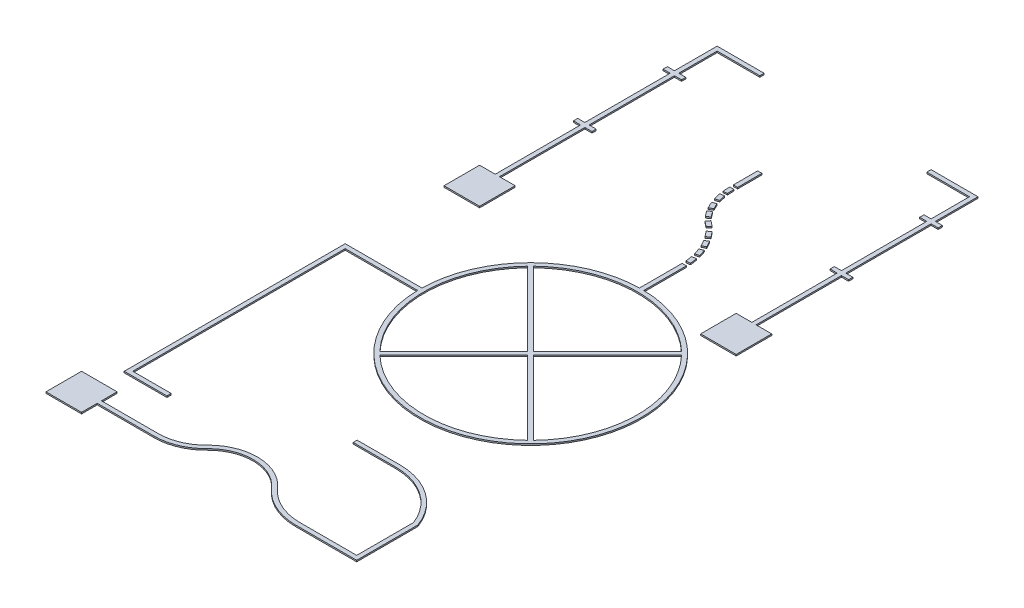
SolidWorks part; units mm, degrees
ref_plane "Front Plane" through (0, 0, 0) normal (0, 0, 1) x (1, 0, 0)
ref_plane "Top Plane" through (0, 0, 0) normal (0, 1, 0) x (1, 0, 0)
ref_plane "Right Plane" through (0, 0, 0) normal (1, 0, 0) x (0, 0, -1)
sketch "Sketch1" plane through (0, 0, 0) normal (0, 1, 0) x (1, 0, 0)
  line L1 (1219.2, -2438.4) -> (-1219.2, -2438.4)
  line L2 (1219.2, -2438.4) -> (1219.2, 2438.4)
  line L3 (1219.2, 2438.4) -> (-1219.2, 2438.4)
  line L4 (-1219.2, -2438.4) -> (-1219.2, 2438.4)
  line L5 (1219.2, -2438.4) -> (-1219.2, 2438.4) construction
  line L6 (1219.2, 2438.4) -> (-1219.2, -2438.4) construction
  point P0 (0, 0)
  dimension "D1" = 4876.8
  dimension "D2" = 2438.4
extrude "Boss-Extrude1" add sketch "Sketch1" along normal blind 100
sketch "Sketch2" plane through (0, 100, 0) normal (0, 1, 0) x (1, 0, 0)
  line L0 (-1219.2, 2438.4) -> (-1219.2, -2438.4) construction
  line L1 (-919.2, -2338.4) -> (-1169.2, -2338.4)
  line L2 (-919.2, -2338.4) -> (-919.2, -2228.4)
  line L3 (-919.2, -2088.4) -> (-1169.2, -2088.4)
  line L4 (-1169.2, -2338.4) -> (-1169.2, -2088.4)
  line L5 (-919.2, -2338.4) -> (-1169.2, -2088.4) construction
  line L6 (-919.2, -2088.4) -> (-1169.2, -2338.4) construction
  line L7 (-1219.2, -2438.4) -> (1219.2, -2438.4) construction
  line L8 (-919.2, -2228.4) -> (-519.2, -2228.4)
  line L9 (-919.2, -2213.4) -> (-874.2776, -2213.4) construction
  line L10 (-919.2, -2198.4) -> (-519.2, -2198.4)
  line L11 (-919.2, -2198.4) -> (-919.2, -2088.4)
  line L12 (518.6973, -2271.9533) -> (948.6973, -2271.9533)
  line L13 (518.6973, -2241.9533) -> (918.6973, -2241.9533)
  line L14 (918.6973, -2241.9533) -> (918.6973, -1841.9533)
  line L15 (948.6973, -2271.9533) -> (948.6973, -1841.9533)
  line L17 (518.6973, -1539.0748) -> (218.6973, -1539.0748)
  line L18 (218.6973, -1539.0748) -> (218.6973, -1567.2032)
  line L19 (218.6973, -1567.2032) -> (518.6973, -1567.2032)
  line L20 (-1019.2, -1938.4) -> (-719.2, -1938.4)
  line L21 (-719.2, -1938.4) -> (-719.2, -1908.4)
  line L22 (-719.2, -1908.4) -> (-989.2, -1908.4)
  line L23 (-989.2, -1908.4) -> (-989.2, -415)
  line L24 (-989.2, -415) -> (-479.8558, -415)
  line L25 (300, -400) -> (-1082.2018, -400) construction
  line L26 (-1019.2, -1938.4) -> (-1019.2, -385)
  line L27 (-1019.2, -385) -> (-479.8558, -385)
  line L28 (300, -400) -> (300, -1150) construction
  line L29 (300, -400) -> (830.3301, -930.3301) construction
  line L30 (819.6179, -940.8301) -> (300, -421.2121)
  line L31 (300, -400) -> (-230.3301, 130.3301) construction
  line L32 (840.8301, -919.6179) -> (321.2121, -400)
  line L33 (300, -400) -> (830.3301, 130.3301) construction
  line L34 (830.3301, 130.3301) -> (-230.3301, -930.3301) construction
  line L35 (-240.8301, -919.6179) -> (278.7879, -400)
  line L36 (840.8301, 119.6179) -> (321.2121, -400)
  line L37 (300, -378.7879) -> (819.6179, 140.8301)
  line L38 (278.7879, -400) -> (-240.8301, 119.6179)
  line L39 (300, -421.2121) -> (-219.6179, -940.8301)
  line L40 (300, -378.7879) -> (-219.6179, 140.8301)
  line L41 (300, -400) -> (300, 350) construction
  line L42 (300, 350) -> (300, 632.1211) construction
  line L43 (285, 379.8558) -> (285, 679.8558)
  line L44 (315, 379.8558) -> (315, 679.8558)
  line L45 (285, 679.8558) -> (315, 679.8558)
  line L47 (283.4854, 707.2433) -> (313.3638, 709.8558)
  line L48 (276.8899, 753.4856) -> (306.3073, 759.3304)
  line L49 (270.3336, 781.5256) -> (299.2927, 789.3304)
  line L50 (255.7416, 825.8982) -> (283.6807, 836.8045)
  line L51 (243.6288, 853.9382) -> (270.7213, 866.8045)
  line L52 (221.3238, 894.9789) -> (246.8572, 910.7139)
  line L53 (202.4819, 923.0189) -> (226.6982, 940.7139)
  line L54 (172.9117, 959.1776) -> (195.0611, 979.4001)
  line L55 (144.8258, 987.2176) -> (165.012, 1009.4001)
  line L57 (104.4289, 1065.1132) -> (81.255, 1046.0708)
  line L58 (77.2262, 1102.6314) -> (51.9232, 1086.5256)
  line L59 (64.2637, 1124.5744) -> (37.9461, 1110.1861)
  line L60 (16.6704, 1155.4) -> (44.5324, 1166.5062)
  line L61 (34.3337, 1195.4) -> (5.6734, 1186.5553)
  line L62 (23.3708, 1240.4268) -> (-6.1476, 1235.1065)
  line L63 (-10.1201, 1262.2983) -> (19.6866, 1265.6449)
  line L64 (-12.6825, 1312.2021) -> (17.3102, 1311.9261)
  line L65 (18.3921, 1337.3888) -> (17.294, 1337.4721)
  line L66 (-12.7, 1337.4721) -> (-12.7, 1508.4)
  line L67 (-12.7, 1508.4) -> (17.294, 1508.4)
  line L68 (17.294, 1508.4) -> (17.294, 1337.4721)
  line L69 (2.297, 1508.4) -> (2.297, 2375.9732) construction
  line L70 (-584.703, 2095.4) -> (-884.703, 2095.4)
  line L71 (-584.703, 2095.4) -> (-584.703, 2125.4)
  line L72 (-584.703, 2125.4) -> (-914.703, 2125.4)
  line L73 (-914.703, 2125.4) -> (-914.703, 1825.4)
  line L75 (-884.703, 1825.4) -> (-884.703, 2095.4)
  line L82 (1219.2, 2438.4) -> (-1219.2, 2438.4) construction
  line L83 (126.2742, 1040.9739) -> (108.6188, 1016.7287)
  line L84 (-914.703, 1795.4) -> (-914.703, 1195.4)
  line L86 (-884.703, 565.4) -> (-884.703, 1165.4)
  line L87 (-884.703, 1825.4) -> (-834.703, 1825.4)
  line L88 (-834.703, 1825.4) -> (-834.703, 1795.4)
  line L89 (-834.703, 1795.4) -> (-884.703, 1795.4)
  line L90 (-884.703, 1195.4) -> (-834.703, 1195.4)
  line L91 (-914.703, 1795.4) -> (-964.703, 1795.4)
  line L92 (-964.703, 1795.4) -> (-964.703, 1825.4)
  line L93 (-964.703, 1825.4) -> (-914.703, 1825.4)
  line L94 (-834.703, 1195.4) -> (-834.703, 1165.4)
  line L95 (-834.703, 1165.4) -> (-884.703, 1165.4)
  line L96 (-899.703, 565.4) -> (-899.703, 505.0509) construction
  line L97 (-914.703, 1165.4) -> (-964.703, 1165.4)
  line L98 (-964.703, 1165.4) -> (-964.703, 1195.4)
  line L99 (-964.703, 1195.4) -> (-914.703, 1195.4)
  line L100 (-884.703, 1195.4) -> (-884.703, 1795.4)
  line L101 (-914.703, 1165.4) -> (-914.703, 565.4)
  line L102 (-884.703, 565.4) -> (-774.703, 565.4)
  line L103 (-774.703, 565.4) -> (-774.703, 315.4)
  line L104 (-774.703, 315.4) -> (-1024.703, 315.4)
  line L105 (-1024.703, 315.4) -> (-1024.703, 565.4)
  line L106 (-1024.703, 565.4) -> (-914.703, 565.4)
  line L107 (17.294, 1337.4721) -> (-12.7, 1337.4721)
  line L108 (17.294, 1311.9263) -> (17.294, 1308.4)
  line L109 (889.297, 565.4) -> (779.297, 565.4)
  line L110 (779.297, 565.4) -> (779.297, 315.4)
  line L111 (779.297, 315.4) -> (1029.297, 315.4)
  line L112 (1029.297, 315.4) -> (1029.297, 565.4)
  line L113 (1029.297, 565.4) -> (919.297, 565.4)
  line L114 (919.297, 1165.4) -> (919.297, 565.4)
  line L115 (919.297, 1165.4) -> (969.297, 1165.4)
  line L116 (969.297, 1165.4) -> (969.297, 1195.4)
  line L117 (969.297, 1195.4) -> (919.297, 1195.4)
  line L118 (919.297, 1795.4) -> (919.297, 1195.4)
  line L119 (919.297, 1795.4) -> (969.297, 1795.4)
  line L120 (969.297, 1795.4) -> (969.297, 1825.4)
  line L121 (969.297, 1825.4) -> (919.297, 1825.4)
  line L122 (919.297, 2125.4) -> (919.297, 1825.4)
  line L123 (589.297, 2125.4) -> (919.297, 2125.4)
  line L124 (589.297, 2095.4) -> (589.297, 2125.4)
  line L125 (589.297, 2095.4) -> (889.297, 2095.4)
  line L126 (889.297, 1825.4) -> (889.297, 2095.4)
  line L127 (889.297, 1825.4) -> (839.297, 1825.4)
  line L128 (839.297, 1825.4) -> (839.297, 1795.4)
  line L129 (839.297, 1795.4) -> (889.297, 1795.4)
  line L130 (889.297, 1195.4) -> (889.297, 1795.4)
  line L131 (889.297, 1195.4) -> (839.297, 1195.4)
  line L132 (839.297, 1195.4) -> (839.297, 1165.4)
  line L133 (839.297, 1165.4) -> (889.297, 1165.4)
  line L134 (889.297, 565.4) -> (889.297, 1165.4)
  arc A0 (-519.2, -2228.4) -> (-256.4254, -2117.5698) centre (-519.2, -1861.47) ccw
  arc A1 (-519.2, -2198.4) -> (-277.9097, -2096.6312) centre (-519.2, -1861.47) ccw
  arc A3 (208.9279, -2130.8016) -> (-256.4254, -2117.5698) centre (-29.8396, -2338.4) ccw
  arc A4 (231.5673, -2111.1176) -> (518.6973, -2241.9533) centre (518.6973, -1861.47) ccw
  arc A5 (208.9279, -2130.8016) -> (518.6973, -2271.9533) centre (518.6973, -1861.47) ccw
  arc A6 (231.5673, -2111.1176) -> (-277.9097, -2096.6312) centre (-29.8396, -2338.4) ccw
  arc A7 (918.6973, -1841.9533) -> (518.6973, -1567.2032) centre (518.6973, -1995.7519) ccw
  arc A8 (948.6973, -1841.9533) -> (518.6973, -1539.0748) centre (518.6973, -1995.7519) ccw
  arc A9 (840.8301, -919.6179) -> (840.8301, 119.6179) centre (300, -400) ccw
  arc A10 (-479.8558, -415) -> (315, 379.8558) centre (300, -400) ccw
  arc A11 (-240.8301, 119.6179) -> (-240.8301, -919.6179) centre (300, -400) ccw
  arc A12 (-219.6179, -940.8301) -> (819.6179, -940.8301) centre (300, -400) ccw
  arc A13 (819.6179, 140.8301) -> (-219.6179, 140.8301) centre (300, -400) ccw
  arc A14 (285, 379.8558) -> (-479.8558, -385) centre (300, -400) ccw
  arc A17 (-12.7, 1308.4) -> (-10.1201, 1262.2983) centre (400.4986, 1308.4) ccw
  arc A18 (17.294, 1308.4) -> (19.6866, 1265.6449) centre (400.4986, 1308.4) ccw
  arc A19 (270.3336, 781.5256) -> (255.7416, 825.8982) centre (-143.9653, 669.8681) ccw
  arc A20 (283.4854, 707.2433) -> (276.8899, 753.4856) centre (-143.9653, 669.8681) ccw
  arc A21 (313.3638, 709.8558) -> (306.3073, 759.3304) centre (-143.9653, 669.8681) ccw
  arc A22 (299.2927, 789.3304) -> (283.6807, 836.8045) centre (-143.9653, 669.8681) ccw
  arc A23 (270.7213, 866.8045) -> (246.8572, 910.7139) centre (-143.9653, 669.8681) ccw
  arc A24 (243.6288, 853.9382) -> (221.3238, 894.9789) centre (-143.9653, 669.8681) ccw
  arc A25 (226.6982, 940.7139) -> (195.0611, 979.4001) centre (-143.9653, 669.8681) ccw
  arc A26 (202.4819, 923.0189) -> (172.9117, 959.1776) centre (-143.9653, 669.8681) ccw
  arc A27 (144.8258, 987.2176) -> (108.6188, 1016.7287) centre (-143.9653, 669.8681) ccw
  arc A28 (165.012, 1009.4001) -> (126.2742, 1040.9739) centre (-143.9653, 669.8681) ccw
  arc A29 (51.9232, 1086.5256) -> (81.255, 1046.0708) centre (400.4986, 1308.4) ccw
  arc A30 (77.2262, 1102.6314) -> (104.4289, 1065.1132) centre (400.4986, 1308.4) ccw
  arc A31 (44.5324, 1166.5062) -> (64.2637, 1124.5744) centre (400.4986, 1308.4) ccw
  arc A32 (16.6704, 1155.4) -> (37.9461, 1110.1861) centre (400.4986, 1308.4) ccw
  arc A33 (23.3708, 1240.4268) -> (34.3337, 1195.4) centre (400.4986, 1308.4) ccw
  arc A34 (-6.1476, 1235.1065) -> (5.6734, 1186.5553) centre (400.4986, 1308.4) ccw
  arc A35 (17.3102, 1311.9261) -> (19.6866, 1265.6449) centre (400.4986, 1308.4) ccw
  arc A36 (-12.6825, 1312.2021) -> (-10.1201, 1262.2983) centre (400.4986, 1308.4) ccw
  arc A38 (77.2262, 1102.6314) -> (104.4289, 1065.1132) centre (400.4986, 1308.4) ccw
  arc A39 (51.9232, 1086.5256) -> (81.255, 1046.0708) centre (400.4986, 1308.4) ccw
  arc A40 (44.5324, 1166.5062) -> (64.2637, 1124.5744) centre (400.4986, 1308.4) ccw
  arc A41 (16.6704, 1155.4) -> (37.9461, 1110.1861) centre (400.4986, 1308.4) ccw
  arc A42 (23.3708, 1240.4268) -> (34.3337, 1195.4) centre (400.4986, 1308.4) ccw
  arc A43 (-6.1476, 1235.1065) -> (5.6734, 1186.5553) centre (400.4986, 1308.4) ccw
  point P0 (-1044.2, -2213.4)
  point P9 (-1044.2, -2338.4)
  line M8 (-1219.2, 2438.4) -> (-1219.2, -2438.4)
  line M9 (-1219.2, -2438.4) -> (1219.2, -2438.4)
  line M10 (1219.2, -2438.4) -> (1219.2, 2438.4)
  line M11 (1219.2, 2438.4) -> (-1219.2, 2438.4)
  dimension "D9" = 673.8601
  dimension "D10" = 733.8601
  dimension "D11" = 632.794
  dimension "D12" = 489.3604
  dimension "D13" = 760.9667
  dimension "D15" = 30
  dimension "D21" = 857.0975
  dimension "D28" = 1500
  dimension "D31" = 1560
  dimension "D1" = 250
  dimension "D2" = 250
  dimension "D3" = 50
  dimension "D4" = 100
  dimension "D5" = 400
  dimension "D6" = 15
  dimension "D7" = 15
  dimension "D8" = 125
  dimension "D14" = 1037.8973
  dimension "D16" = 30
  dimension "D17" = 30
  dimension "D18" = 400
  dimension "D19" = 430
  dimension "D20" = 400
  dimension "D22" = 400
  dimension "D23" = 300
  dimension "D24" = 300
  dimension "D25" = 270
  dimension "D26" = 30
  dimension "D27" = 150
  dimension "D29" = 300
  dimension "D30" = 400
  dimension "D32" = 15
  dimension "D33" = 15
  dimension "D34" = 100
  dimension "D35" = 45
  dimension "D36" = 15
  dimension "D37" = 45
  dimension "D38" = 15
  dimension "D39" = 15
  dimension "D40" = 15
  dimension "D41" = 1499.7
  dimension "D42" = 519.6179
  dimension "D43" = 45
  dimension "D44" = 15
  dimension "D45" = 15
  dimension "D46" = 15
  dimension "D47" = 15
  dimension "D48" = 1499.7
  dimension "D49" = 15
  dimension "D50" = 15
  dimension "D51" = 300
  dimension "D52" = 30
  dimension "D53" = 50
  dimension "D54" = 30
  dimension "D55" = 50
  dimension "D56" = 30
  dimension "D57" = 50
  dimension "D58" = 30
  dimension "D59" = 50
  dimension "D60" = 30
  dimension "D61" = 50
  dimension "D62" = 1206.5
  dimension "D63" = 50
  dimension "D64" = 40
  dimension "D65" = 50
  dimension "D66" = 40
  dimension "D67" = 50
  dimension "D68" = 40
  dimension "D69" = 50
  dimension "D70" = 40
  dimension "D71" = 200
  dimension "D72" = 29.994
  dimension "D73" = 587
  dimension "D74" = 30
  dimension "D75" = 587
  dimension "D76" = 300
  dimension "D77" = 30
  dimension "D78" = 930
  dimension "D79" = 300
  dimension "D80" = 1260
  dimension "D81" = 30
  dimension "D82" = 50
  dimension "D83" = 50
  dimension "D84" = 330
  dimension "D85" = 30
  dimension "D86" = 887
  dimension "D87" = 30
  dimension "D88" = 30
  dimension "D89" = 50
  dimension "D90" = 50
  dimension "D91" = 600
  dimension "D92" = 30
  dimension "D93" = 600
  dimension "D94" = 125
  dimension "D95" = 125
  dimension "D96" = 250
  dimension "D97" = 110
extrude "Cut-Extrude1" cut sketch "Sketch2" against normal up to surface (100 mm away) contours A36 L64 A35 A18 L63 A17 A34 L62 A33 L61 A32 L60 A31 L59 A28 L55 A27 L83 A22 L49 A19 L50 A21 L47 A20 L48 A14 L43 L45 L44 A10 L24 L23 L22 L21 L20 L26 L27 M11 M8 M9 M10 | L32 A9 L36 | L39 A12 L30 | L38 A11 L35 | L37 A13 L40
sketch "Sketch3" plane through (0, 0, 0) normal (0, -1, 0) x (1, 0, 0)
  line L14 (948.6973, 1841.9533) -> (948.6973, 2271.9533)
  line L15 (948.6973, 2271.9533) -> (518.6973, 2271.9533)
  line L16 (-519.2, 2228.4) -> (-919.2, 2228.4)
  line L17 (-919.2, 2228.4) -> (-919.2, 2338.4)
  line L18 (-919.2, 2338.4) -> (-1169.2, 2338.4)
  line L19 (-1169.2, 2338.4) -> (-1169.2, 2088.4)
  line L20 (-1169.2, 2088.4) -> (-919.2, 2088.4)
  line L21 (-919.2, 2088.4) -> (-919.2, 2198.4)
  line L22 (-919.2, 2198.4) -> (-519.2, 2198.4)
  line L23 (518.6973, 2241.9533) -> (918.6973, 2241.9533)
  line L24 (918.6973, 2241.9533) -> (918.6973, 1841.9533)
  line L25 (518.6973, 1567.2032) -> (218.6973, 1567.2032)
  line L26 (218.6973, 1567.2032) -> (218.6973, 1539.0748)
  line L27 (218.6973, 1539.0748) -> (518.6973, 1539.0748)
  line L28 (948.6973, 1841.9533) -> (948.6973, 2271.9533)
  line L29 (948.6973, 2271.9533) -> (518.6973, 2271.9533)
  line L30 (-519.2, 2228.4) -> (-919.2, 2228.4)
  line L31 (-919.2, 2228.4) -> (-919.2, 2338.4)
  line L32 (-919.2, 2338.4) -> (-1169.2, 2338.4)
  line L33 (-1169.2, 2338.4) -> (-1169.2, 2088.4)
  line L34 (-1169.2, 2088.4) -> (-919.2, 2088.4)
  line L35 (-919.2, 2088.4) -> (-919.2, 2198.4)
  line L36 (-919.2, 2198.4) -> (-519.2, 2198.4)
  line L37 (518.6973, 2241.9533) -> (918.6973, 2241.9533)
  line L38 (918.6973, 2241.9533) -> (918.6973, 1841.9533)
  line L39 (518.6973, 1567.2032) -> (218.6973, 1567.2032)
  line L40 (218.6973, 1567.2032) -> (218.6973, 1539.0748)
  line L41 (218.6973, 1539.0748) -> (518.6973, 1539.0748)
  arc A8 (518.6973, 1539.0748) -> (948.6973, 1841.9533) centre (518.6973, 1995.7519) ccw
  arc A9 (518.6973, 2271.9533) -> (208.9279, 2130.8016) centre (518.6973, 1861.47) ccw
  arc A10 (-256.4254, 2117.5698) -> (208.9279, 2130.8016) centre (-29.8396, 2338.4) ccw
  arc A11 (-256.4254, 2117.5698) -> (-519.2, 2228.4) centre (-519.2, 1861.47) ccw
  arc A12 (-277.9097, 2096.6312) -> (-519.2, 2198.4) centre (-519.2, 1861.47) ccw
  arc A13 (-277.9097, 2096.6312) -> (231.5673, 2111.1176) centre (-29.8396, 2338.4) ccw
  arc A14 (518.6973, 2241.9533) -> (231.5673, 2111.1176) centre (518.6973, 1861.47) ccw
  arc A15 (518.6973, 1567.2032) -> (918.6973, 1841.9533) centre (518.6973, 1995.7519) ccw
  arc A16 (518.6973, 1539.0748) -> (948.6973, 1841.9533) centre (518.6973, 1995.7519) ccw
  arc A17 (518.6973, 2271.9533) -> (208.9279, 2130.8016) centre (518.6973, 1861.47) ccw
  arc A18 (-256.4254, 2117.5698) -> (208.9279, 2130.8016) centre (-29.8396, 2338.4) ccw
  arc A19 (-256.4254, 2117.5698) -> (-519.2, 2228.4) centre (-519.2, 1861.47) ccw
  arc A20 (-277.9097, 2096.6312) -> (-519.2, 2198.4) centre (-519.2, 1861.47) ccw
  arc A21 (-277.9097, 2096.6312) -> (231.5673, 2111.1176) centre (-29.8396, 2338.4) ccw
  arc A22 (518.6973, 2241.9533) -> (231.5673, 2111.1176) centre (518.6973, 1861.47) ccw
  arc A23 (518.6973, 1567.2032) -> (918.6973, 1841.9533) centre (518.6973, 1995.7519) ccw
  dimension "D1" = 0
extrude "Cut-Extrude2" cut sketch "Sketch3" against normal offset from surface (90 mm away) 10 up to face at (-36.8998, 100, 2039.063)
sketch "Sketch4" plane through (0, 0, 0) normal (0, -1, 0) x (1, 0, 0)
  line L10 (285, -379.8558) -> (285, -679.8558)
  line L11 (285, -679.8558) -> (315, -679.8558)
  line L12 (315, -679.8558) -> (315, -379.8558)
  line L13 (-479.8558, 415) -> (-989.2, 415)
  line L14 (-989.2, 415) -> (-989.2, 1908.4)
  line L15 (-989.2, 1908.4) -> (-719.2, 1908.4)
  line L16 (-719.2, 1908.4) -> (-719.2, 1938.4)
  line L17 (-719.2, 1938.4) -> (-1019.2, 1938.4)
  line L18 (-1019.2, 1938.4) -> (-1019.2, 385)
  line L19 (-1019.2, 385) -> (-479.8558, 385)
  line L20 (285, -379.8558) -> (285, -679.8558)
  line L21 (285, -679.8558) -> (315, -679.8558)
  line L22 (315, -679.8558) -> (315, -379.8558)
  line L23 (-479.8558, 415) -> (-989.2, 415)
  line L24 (-989.2, 415) -> (-989.2, 1908.4)
  line L25 (-989.2, 1908.4) -> (-719.2, 1908.4)
  line L26 (-719.2, 1908.4) -> (-719.2, 1938.4)
  line L27 (-719.2, 1938.4) -> (-1019.2, 1938.4)
  line L28 (-1019.2, 1938.4) -> (-1019.2, 385)
  line L29 (-1019.2, 385) -> (-479.8558, 385)
  arc A2 (-479.8558, 385) -> (285, -379.8558) centre (300, 400) ccw
  arc A3 (315, -379.8558) -> (-479.8558, 415) centre (300, 400) ccw
  arc A4 (-479.8558, 385) -> (285, -379.8558) centre (300, 400) ccw
  arc A5 (315, -379.8558) -> (-479.8558, 415) centre (300, 400) ccw
  dimension "D1" = 0
extrude "Cut-Extrude3" cut sketch "Sketch4" against normal offset from surface (90 mm away) 10 up to face at (300, 100, 837.3474)
sketch "Sketch5" plane through (0, 0, 0) normal (0, -1, 0) x (1, 0, 0)
  line L26 (779.297, -565.4) -> (889.297, -565.4)
  line L27 (889.297, -565.4) -> (889.297, -1165.4)
  line L28 (889.297, -1165.4) -> (839.297, -1165.4)
  line L29 (839.297, -1165.4) -> (839.297, -1195.4)
  line L30 (839.297, -1195.4) -> (889.297, -1195.4)
  line L31 (889.297, -1195.4) -> (889.297, -1795.4)
  line L32 (889.297, -1795.4) -> (839.297, -1795.4)
  line L33 (839.297, -1795.4) -> (839.297, -1825.4)
  line L34 (839.297, -1825.4) -> (889.297, -1825.4)
  line L35 (889.297, -1825.4) -> (889.297, -2095.4)
  line L36 (889.297, -2095.4) -> (589.297, -2095.4)
  line L37 (589.297, -2095.4) -> (589.297, -2125.4)
  line L38 (589.297, -2125.4) -> (919.297, -2125.4)
  line L39 (919.297, -2125.4) -> (919.297, -1825.4)
  line L40 (919.297, -1825.4) -> (969.297, -1825.4)
  line L41 (969.297, -1825.4) -> (969.297, -1795.4)
  line L42 (969.297, -1795.4) -> (919.297, -1795.4)
  line L43 (919.297, -1795.4) -> (919.297, -1195.4)
  line L44 (919.297, -1195.4) -> (969.297, -1195.4)
  line L45 (969.297, -1195.4) -> (969.297, -1165.4)
  line L46 (969.297, -1165.4) -> (919.297, -1165.4)
  line L47 (919.297, -1165.4) -> (919.297, -565.4)
  line L48 (919.297, -565.4) -> (1029.297, -565.4)
  line L49 (1029.297, -565.4) -> (1029.297, -315.4)
  line L50 (1029.297, -315.4) -> (779.297, -315.4)
  line L51 (779.297, -315.4) -> (779.297, -565.4)
  line L52 (779.297, -565.4) -> (889.297, -565.4)
  line L53 (889.297, -565.4) -> (889.297, -1165.4)
  line L54 (889.297, -1165.4) -> (839.297, -1165.4)
  line L55 (839.297, -1165.4) -> (839.297, -1195.4)
  line L56 (839.297, -1195.4) -> (889.297, -1195.4)
  line L57 (889.297, -1195.4) -> (889.297, -1795.4)
  line L58 (889.297, -1795.4) -> (839.297, -1795.4)
  line L59 (839.297, -1795.4) -> (839.297, -1825.4)
  line L60 (839.297, -1825.4) -> (889.297, -1825.4)
  line L61 (889.297, -1825.4) -> (889.297, -2095.4)
  line L62 (889.297, -2095.4) -> (589.297, -2095.4)
  line L63 (589.297, -2095.4) -> (589.297, -2125.4)
  line L64 (589.297, -2125.4) -> (919.297, -2125.4)
  line L65 (919.297, -2125.4) -> (919.297, -1825.4)
  line L66 (919.297, -1825.4) -> (969.297, -1825.4)
  line L67 (969.297, -1825.4) -> (969.297, -1795.4)
  line L68 (969.297, -1795.4) -> (919.297, -1795.4)
  line L69 (919.297, -1795.4) -> (919.297, -1195.4)
  line L70 (919.297, -1195.4) -> (969.297, -1195.4)
  line L71 (969.297, -1195.4) -> (969.297, -1165.4)
  line L72 (969.297, -1165.4) -> (919.297, -1165.4)
  line L73 (919.297, -1165.4) -> (919.297, -565.4)
  line L74 (919.297, -565.4) -> (1029.297, -565.4)
  line L75 (1029.297, -565.4) -> (1029.297, -315.4)
  line L76 (1029.297, -315.4) -> (779.297, -315.4)
  line L77 (779.297, -315.4) -> (779.297, -565.4)
  dimension "D1" = 0
extrude "Cut-Extrude4" cut sketch "Sketch5" against normal offset from surface (90 mm away) 10 up to face at (880.0662, 100, -1356.1692)
sketch "Sketch6" plane through (0, 0, 0) normal (0, -1, 0) x (1, 0, 0)
  line L26 (-774.703, -315.4) -> (-1024.703, -315.4)
  line L27 (-1024.703, -315.4) -> (-1024.703, -565.4)
  line L28 (-1024.703, -565.4) -> (-914.703, -565.4)
  line L29 (-914.703, -565.4) -> (-914.703, -1165.4)
  line L30 (-914.703, -1165.4) -> (-964.703, -1165.4)
  line L31 (-964.703, -1165.4) -> (-964.703, -1195.4)
  line L32 (-964.703, -1195.4) -> (-914.703, -1195.4)
  line L33 (-914.703, -1195.4) -> (-914.703, -1795.4)
  line L34 (-914.703, -1795.4) -> (-964.703, -1795.4)
  line L35 (-964.703, -1795.4) -> (-964.703, -1825.4)
  line L36 (-964.703, -1825.4) -> (-914.703, -1825.4)
  line L37 (-914.703, -1825.4) -> (-914.703, -2125.4)
  line L38 (-914.703, -2125.4) -> (-584.703, -2125.4)
  line L39 (-584.703, -2125.4) -> (-584.703, -2095.4)
  line L40 (-584.703, -2095.4) -> (-884.703, -2095.4)
  line L41 (-884.703, -2095.4) -> (-884.703, -1825.4)
  line L42 (-884.703, -1825.4) -> (-834.703, -1825.4)
  line L43 (-834.703, -1825.4) -> (-834.703, -1795.4)
  line L44 (-834.703, -1795.4) -> (-884.703, -1795.4)
  line L45 (-884.703, -1795.4) -> (-884.703, -1195.4)
  line L46 (-884.703, -1195.4) -> (-834.703, -1195.4)
  line L47 (-834.703, -1195.4) -> (-834.703, -1165.4)
  line L48 (-834.703, -1165.4) -> (-884.703, -1165.4)
  line L49 (-884.703, -1165.4) -> (-884.703, -565.4)
  line L50 (-884.703, -565.4) -> (-774.703, -565.4)
  line L51 (-774.703, -565.4) -> (-774.703, -315.4)
  line L52 (-774.703, -315.4) -> (-1024.703, -315.4)
  line L53 (-1024.703, -315.4) -> (-1024.703, -565.4)
  line L54 (-1024.703, -565.4) -> (-914.703, -565.4)
  line L55 (-914.703, -565.4) -> (-914.703, -1165.4)
  line L56 (-914.703, -1165.4) -> (-964.703, -1165.4)
  line L57 (-964.703, -1165.4) -> (-964.703, -1195.4)
  line L58 (-964.703, -1195.4) -> (-914.703, -1195.4)
  line L59 (-914.703, -1195.4) -> (-914.703, -1795.4)
  line L60 (-914.703, -1795.4) -> (-964.703, -1795.4)
  line L61 (-964.703, -1795.4) -> (-964.703, -1825.4)
  line L62 (-964.703, -1825.4) -> (-914.703, -1825.4)
  line L63 (-914.703, -1825.4) -> (-914.703, -2125.4)
  line L64 (-914.703, -2125.4) -> (-584.703, -2125.4)
  line L65 (-584.703, -2125.4) -> (-584.703, -2095.4)
  line L66 (-584.703, -2095.4) -> (-884.703, -2095.4)
  line L67 (-884.703, -2095.4) -> (-884.703, -1825.4)
  line L68 (-884.703, -1825.4) -> (-834.703, -1825.4)
  line L69 (-834.703, -1825.4) -> (-834.703, -1795.4)
  line L70 (-834.703, -1795.4) -> (-884.703, -1795.4)
  line L71 (-884.703, -1795.4) -> (-884.703, -1195.4)
  line L72 (-884.703, -1195.4) -> (-834.703, -1195.4)
  line L73 (-834.703, -1195.4) -> (-834.703, -1165.4)
  line L74 (-834.703, -1165.4) -> (-884.703, -1165.4)
  line L75 (-884.703, -1165.4) -> (-884.703, -565.4)
  line L76 (-884.703, -565.4) -> (-774.703, -565.4)
  line L77 (-774.703, -565.4) -> (-774.703, -315.4)
  dimension "D1" = 0
extrude "Cut-Extrude5" cut sketch "Sketch6" against normal offset from surface (90 mm away) 10 up to face at (-875.4722, 100, -1356.1692)
sketch "Sketch7" plane through (0, 0, 0) normal (0, -1, 0) x (1, 0, 0)
  line L2 (313.3638, -709.8558) -> (283.4854, -707.2433)
  line L3 (276.8899, -753.4856) -> (306.3073, -759.3304)
  line L4 (313.3638, -709.8558) -> (283.4854, -707.2433)
  line L5 (276.8899, -753.4856) -> (306.3073, -759.3304)
  arc A2 (306.3073, -759.3304) -> (313.3638, -709.8558) centre (-143.9653, -669.8681) ccw
  arc A3 (276.8899, -753.4856) -> (283.4854, -707.2433) centre (-143.9653, -669.8681) ccw
  arc A4 (306.3073, -759.3304) -> (313.3638, -709.8558) centre (-143.9653, -669.8681) ccw
  arc A5 (276.8899, -753.4856) -> (283.4854, -707.2433) centre (-143.9653, -669.8681) ccw
  dimension "D1" = 0
extrude "Cut-Extrude6" cut sketch "Sketch7" against normal offset from surface (90 mm away) 10 up to face at (295.3374, 100, -732.5252)
sketch "Sketch8" plane through (0, 0, 0) normal (0, -1, 0) x (1, 0, 0)
  line L2 (299.2927, -789.3304) -> (270.3336, -781.5256)
  line L3 (255.7416, -825.8982) -> (283.6807, -836.8045)
  line L4 (299.2927, -789.3304) -> (270.3336, -781.5256)
  line L5 (255.7416, -825.8982) -> (283.6807, -836.8045)
  line L6 (270.7213, -866.8045) -> (243.6288, -853.9382)
  line L7 (221.3238, -894.9789) -> (246.8572, -910.7139)
  line L8 (270.7213, -866.8045) -> (243.6288, -853.9382)
  line L9 (221.3238, -894.9789) -> (246.8572, -910.7139)
  line L10 (226.6982, -940.7139) -> (202.4819, -923.0189)
  line L11 (172.9117, -959.1776) -> (195.0611, -979.4001)
  line L12 (226.6982, -940.7139) -> (202.4819, -923.0189)
  line L13 (172.9117, -959.1776) -> (195.0611, -979.4001)
  line L14 (165.012, -1009.4001) -> (144.8258, -987.2176)
  line L15 (108.6188, -1016.7287) -> (126.2742, -1040.9739)
  line L16 (165.012, -1009.4001) -> (144.8258, -987.2176)
  line L17 (108.6188, -1016.7287) -> (126.2742, -1040.9739)
  line L18 (51.9232, -1086.5256) -> (77.2262, -1102.6314)
  line L19 (104.4289, -1065.1132) -> (81.255, -1046.0708)
  line L20 (51.9232, -1086.5256) -> (77.2262, -1102.6314)
  line L21 (104.4289, -1065.1132) -> (81.255, -1046.0708)
  line L22 (16.6704, -1155.4) -> (44.5324, -1166.5062)
  line L23 (64.2637, -1124.5744) -> (37.9461, -1110.1861)
  line L24 (16.6704, -1155.4) -> (44.5324, -1166.5062)
  line L25 (64.2637, -1124.5744) -> (37.9461, -1110.1861)
  line L26 (-6.1476, -1235.1065) -> (23.3708, -1240.4268)
  line L27 (34.3337, -1195.4) -> (5.6734, -1186.5553)
  line L28 (-6.1476, -1235.1065) -> (23.3708, -1240.4268)
  line L29 (34.3337, -1195.4) -> (5.6734, -1186.5553)
  line L30 (-12.6825, -1312.2021) -> (17.3102, -1311.9261)
  line L31 (19.6866, -1265.6449) -> (-10.1201, -1262.2983)
  line L32 (-12.6825, -1312.2021) -> (17.3102, -1311.9261)
  line L33 (19.6866, -1265.6449) -> (-10.1201, -1262.2983)
  line L36 (-12.7, -1508.4) -> (17.294, -1508.4)
  line L37 (17.294, -1508.4) -> (17.294, -1337.4721)
  line L38 (17.294, -1337.4721) -> (-12.7, -1337.4721)
  line L39 (-12.7, -1337.4721) -> (-12.7, -1508.4)
  line L40 (-12.7, -1508.4) -> (17.294, -1508.4)
  line L41 (17.294, -1508.4) -> (17.294, -1337.4721)
  line L42 (17.294, -1337.4721) -> (-12.7, -1337.4721)
  line L43 (-12.7, -1337.4721) -> (-12.7, -1508.4)
  arc A2 (283.6807, -836.8045) -> (299.2927, -789.3304) centre (-143.9653, -669.8681) ccw
  arc A3 (255.7416, -825.8982) -> (270.3336, -781.5256) centre (-143.9653, -669.8681) ccw
  arc A4 (283.6807, -836.8045) -> (299.2927, -789.3304) centre (-143.9653, -669.8681) ccw
  arc A5 (255.7416, -825.8982) -> (270.3336, -781.5256) centre (-143.9653, -669.8681) ccw
  arc A6 (221.3238, -894.9789) -> (243.6288, -853.9382) centre (-143.9653, -669.8681) ccw
  arc A7 (246.8572, -910.7139) -> (270.7213, -866.8045) centre (-143.9653, -669.8681) ccw
  arc A8 (221.3238, -894.9789) -> (243.6288, -853.9382) centre (-143.9653, -669.8681) ccw
  arc A9 (246.8572, -910.7139) -> (270.7213, -866.8045) centre (-143.9653, -669.8681) ccw
  arc A10 (172.9117, -959.1776) -> (202.4819, -923.0189) centre (-143.9653, -669.8681) ccw
  arc A11 (195.0611, -979.4001) -> (226.6982, -940.7139) centre (-143.9653, -669.8681) ccw
  arc A12 (172.9117, -959.1776) -> (202.4819, -923.0189) centre (-143.9653, -669.8681) ccw
  arc A13 (195.0611, -979.4001) -> (226.6982, -940.7139) centre (-143.9653, -669.8681) ccw
  arc A14 (126.2742, -1040.9739) -> (165.012, -1009.4001) centre (-143.9653, -669.8681) ccw
  arc A15 (108.6188, -1016.7287) -> (144.8258, -987.2176) centre (-143.9653, -669.8681) ccw
  arc A16 (126.2742, -1040.9739) -> (165.012, -1009.4001) centre (-143.9653, -669.8681) ccw
  arc A17 (108.6188, -1016.7287) -> (144.8258, -987.2176) centre (-143.9653, -669.8681) ccw
  arc A18 (104.4289, -1065.1132) -> (77.2262, -1102.6314) centre (400.4986, -1308.4) ccw
  arc A19 (81.255, -1046.0708) -> (51.9232, -1086.5256) centre (400.4986, -1308.4) ccw
  arc A20 (104.4289, -1065.1132) -> (77.2262, -1102.6314) centre (400.4986, -1308.4) ccw
  arc A21 (81.255, -1046.0708) -> (51.9232, -1086.5256) centre (400.4986, -1308.4) ccw
  arc A22 (37.9461, -1110.1861) -> (16.6704, -1155.4) centre (400.4986, -1308.4) ccw
  arc A23 (64.2637, -1124.5744) -> (44.5324, -1166.5062) centre (400.4986, -1308.4) ccw
  arc A24 (37.9461, -1110.1861) -> (16.6704, -1155.4) centre (400.4986, -1308.4) ccw
  arc A25 (64.2637, -1124.5744) -> (44.5324, -1166.5062) centre (400.4986, -1308.4) ccw
  arc A26 (5.6734, -1186.5553) -> (-6.1476, -1235.1065) centre (400.4986, -1308.4) ccw
  arc A27 (34.3337, -1195.4) -> (23.3708, -1240.4268) centre (400.4986, -1308.4) ccw
  arc A28 (5.6734, -1186.5553) -> (-6.1476, -1235.1065) centre (400.4986, -1308.4) ccw
  arc A29 (34.3337, -1195.4) -> (23.3708, -1240.4268) centre (400.4986, -1308.4) ccw
  arc A30 (-10.1201, -1262.2983) -> (-12.6825, -1312.2021) centre (400.4986, -1308.4) ccw
  arc A31 (19.6866, -1265.6449) -> (17.3102, -1311.9261) centre (400.4986, -1308.4) ccw
  arc A32 (-10.1201, -1262.2983) -> (-12.6825, -1312.2021) centre (400.4986, -1308.4) ccw
  arc A33 (19.6866, -1265.6449) -> (17.3102, -1311.9261) centre (400.4986, -1308.4) ccw
  dimension "D1" = 0
  dimension "D2" = 0
  dimension "D3" = 0
  dimension "D4" = 0
  dimension "D5" = 0
  dimension "D6" = 0
  dimension "D7" = 0
  dimension "D8" = 0
  dimension "D9" = 0
extrude "Cut-Extrude7" cut sketch "Sketch8" against normal offset from surface (90 mm away) 10 up to face at (2.297, 100, -1422.9361)
